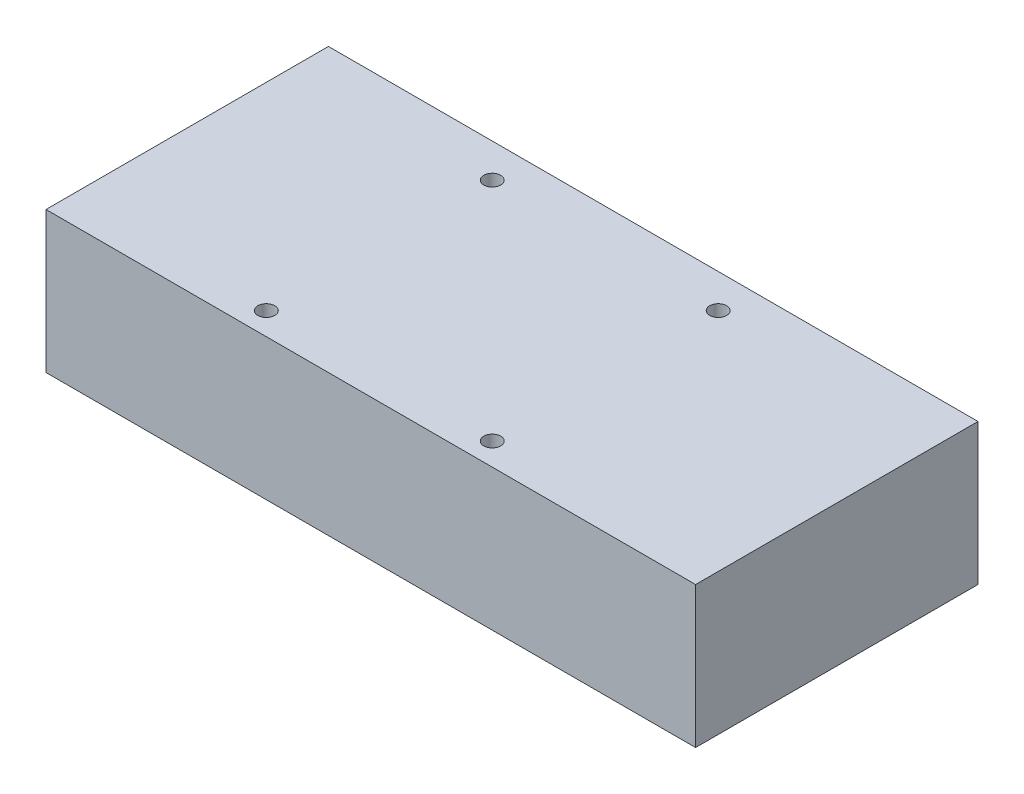
SolidWorks part; units mm, degrees
ref_plane "Front Plane" through (0, 0, 0) normal (0, 0, 1) x (1, 0, 0)
ref_plane "Top Plane" through (0, 0, 0) normal (0, 1, 0) x (1, 0, 0)
ref_plane "Right Plane" through (0, 0, 0) normal (1, 0, 0) x (0, 0, -1)
sketch "Sketch1" plane through (0, 0, 0) normal (0, 1, 0) x (1, 0, 0)
  line L1 (-67.3647, -27.0655) -> (32.6353, -27.0655) construction
  line L2 (-67.3647, -27.0655) -> (-67.3647, 22.9345) construction
  line L3 (-67.3647, 22.9345) -> (32.6353, 22.9345) construction
  line L4 (32.6353, -27.0655) -> (32.6353, 22.9345) construction
  line L5 (42.6353, 22.9345) -> (-72.3647, 22.9345)
  line L6 (42.6353, 22.9345) -> (42.6353, -27.0655)
  line L7 (42.6353, -27.0655) -> (-72.3647, -27.0655)
  line L8 (-72.3647, 22.9345) -> (-72.3647, -27.0655)
  circle A0 centre (-37.3647, 16.9345) radius 1.5
  circle A1 centre (2.6353, 16.9345) radius 1.5
  circle A2 centre (2.6353, -23.0655) radius 1.5
  circle A3 centre (-37.3647, -23.0655) radius 1.5
  dimension "D5" = 3
  dimension "D6" = 3
  dimension "D7" = 3
  dimension "D8" = 3
  dimension "D1" = 100
  dimension "D2" = 50
  dimension "D3" = 115
  dimension "D4" = 5
  dimension "D9" = 30
  dimension "D10" = 30
  dimension "D11" = 30
  dimension "D12" = 30
  dimension "D13" = 4
  dimension "D14" = 4
  dimension "D15" = 6
  dimension "D16" = 6
extrude "Boss-Extrude1" add sketch "Sketch1" along normal blind 25
